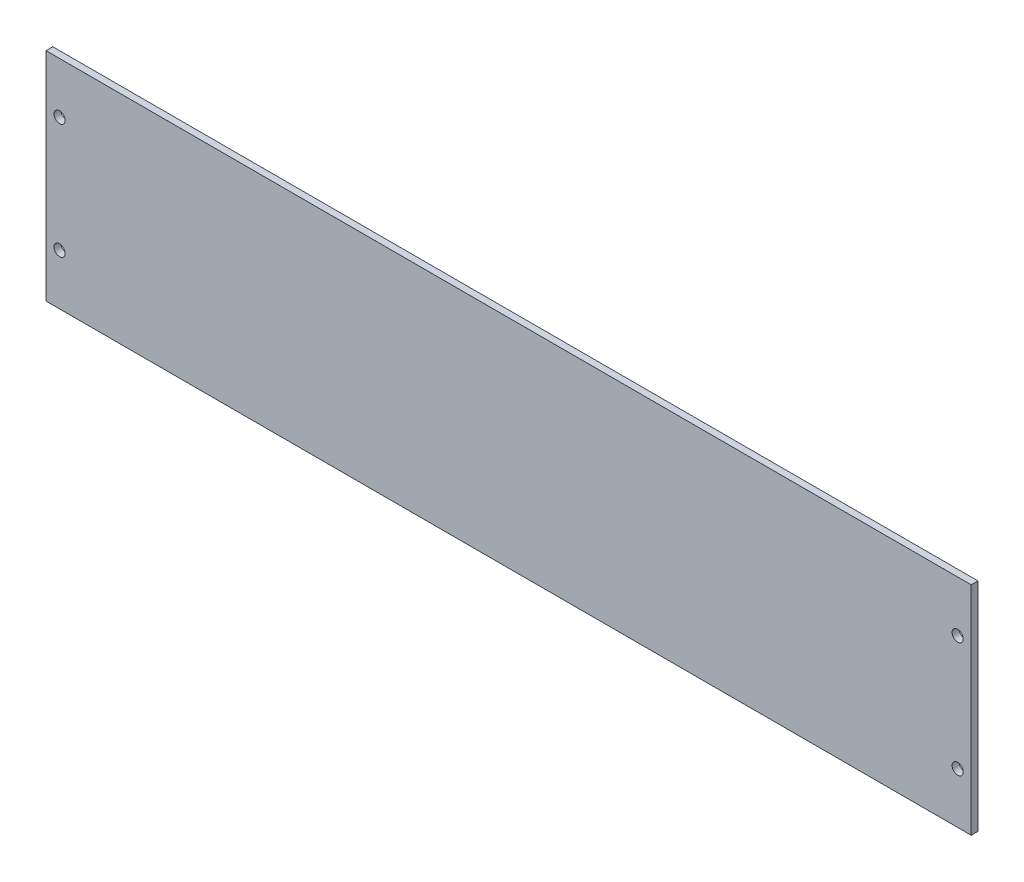
SolidWorks part; units mm, degrees
ref_plane "Plan de face" through (0, 0, 0) normal (0, 0, 1) x (1, 0, 0)
ref_plane "Plan de dessus" through (0, 0, 0) normal (0, 1, 0) x (1, 0, 0)
ref_plane "Plan de droite" through (0, 0, 0) normal (1, 0, 0) x (0, 0, -1)
sketch "Esquisse1" plane through (0, 0, 0) normal (0, 0, 1) x (1, 0, 0)
  line L1 (-273, -64) -> (273, -64)
  line L2 (-273, -64) -> (-273, 64)
  line L3 (-273, 64) -> (273, 64)
  line L4 (273, -64) -> (273, 64)
  line L5 (-273, -64) -> (273, 64) construction
  line L6 (-273, 64) -> (273, -64) construction
  point P0 (0, 0)
  dimension "D1" = 128
  dimension "D2" = 546
extrude "Boss.-Extru.1" add sketch "Esquisse1" along normal blind 4
sketch "Esquisse2" plane through (0, 0, 0) normal (0, 0, -1) x (-1, 0, 0)
  line L0 (273, -64) -> (-273, -64) construction
  line L1 (265, -56) -> (-265, -56) construction
  line L2 (265, -56) -> (265, 56) construction
  line L3 (265, 56) -> (-265, 56) construction
  line L4 (-265, -56) -> (-265, 56) construction
  line L5 (265, -56) -> (-265, 56) construction
  line L6 (265, 56) -> (-265, -56) construction
  line L7 (-273, -64) -> (-273, 64) construction
  line L8 (-153.9304, 0) -> (204.6118, 0) construction
  line L9 (0, -141.2759) -> (0, 199.6584) construction
  point P0 (0, 0)
  point P14 (-265, -34)
  point P15 (-265, 34)
  point P16 (265, -34)
  point P17 (265, 34)
  point P18 (0, 56)
  dimension "D1" = 8
  dimension "D2" = 8
  dimension "D3" = 30
hole_wizard "Dégagement M61" positions "Esquisse3D1" profile "Esquisse3" hole size "M6" standard "ISO" end condition through all
sketch3d "Esquisse3D1"
  point P3 (-265, 34, 0)
  point P6 (-265, -34, 0)
  point P9 (265, -34, 0)
  point P12 (265, 34, 0)
sketch "Esquisse3" plane through (-265, 34, 0) normal (1, 0, 0) x (0, 1, 0)
  line L0 (0, 0) -> (0, 4)
  line L1 (0, 4) -> (3.3, 4)
  line L2 (3.3, 4) -> (3.3, 0)
  line L5 (3.3, 0) -> (0, 0)
  line L11 (0, -6.35) -> (0, 107.95) construction
  dimension "Diamètre du perçage jusqu'au prochain" = 6.6
  dimension "Profondeur du perçage jusqu'au prochain" = 4
